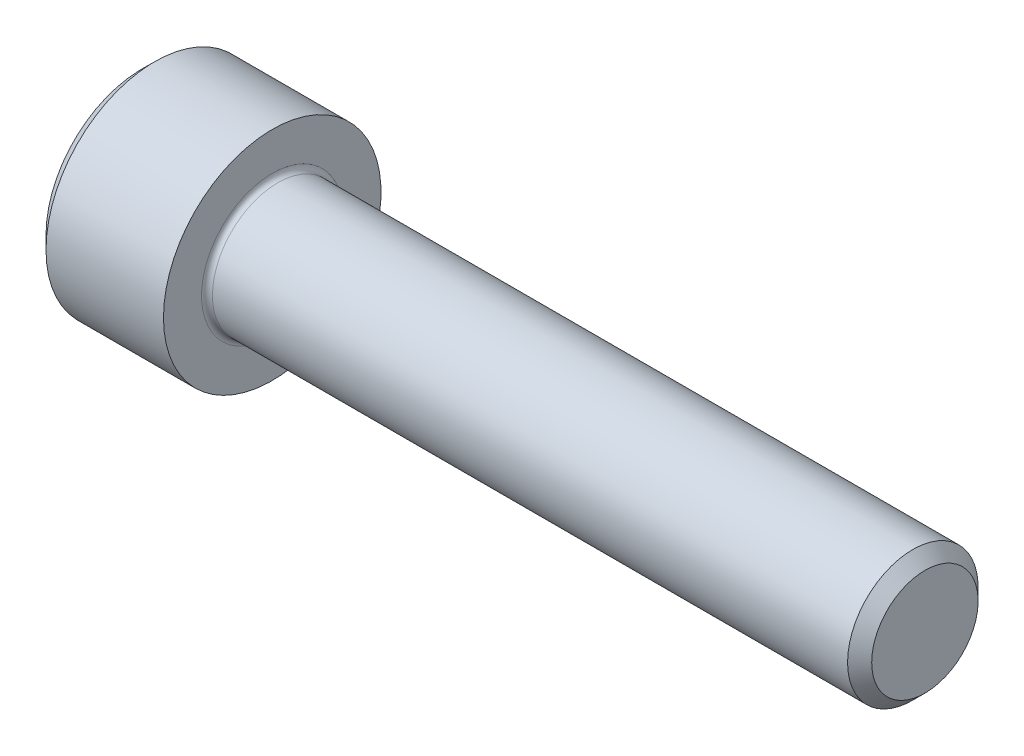
SolidWorks part; units mm, degrees
revolve "Base-Revolve" add sketch "BodySke"
sketch "BodySke" plane through (0, 0, 0) normal (0, 0, 1) x (1, 0, 0)
  line L0 (0, 0) -> (0, 4.4)
  line L1 (0.6, 5) -> (6, 5)
  line L2 (6, 5) -> (6, 3)
  line L3 (6, 3) -> (35.4455, 3)
  line L4 (36, 2.4455) -> (36, 0)
  line L5 (36, 0) -> (0, 0)
  line L6 (-31.75, 0) -> (127, 0) construction
  line L7 (0, 4.4) -> (0.6, 5)
  line L8 (36, 2.4455) -> (35.4455, 3)
  line L9 (0, -4.4) -> (0.6, -5) construction
  line L10 (36, -2.4455) -> (35.4455, -3) construction
  line L11 (7, 1.6185) -> (7, -4.7315) construction
  line L12 (6, 1.6185) -> (6, -4.7315) construction
  line L13 (-14, 1.6185) -> (-14, -4.7315) construction
  dimension "Diameter" = 6
  dimension "Head_ht" = 6
  dimension "Length" = 30
  dimension "Body_ch_ang" = 45
  dimension "Head_dia" = 10
  dimension "Head_ch_ang" = 45
  dimension "Minor_dia" = 4.891
  dimension "Advance" = 1
  dimension "Thread_nom" = 30
  dimension "Thread_length" = 50
  dimension "Head_ch_ht" = 0.6
cosmetic thread "ThreadCosmetic" [suppressed]
fillet "Fillet1" radius 0.25 1 edges at (6, 0, 3)
ref_plane "Plane1" through (0, 0, 0) normal (0, 0, 1) x (1, 0, 0)
ref_plane "Plane2" through (0, 0, 0) normal (0, 1, 0) x (1, 0, 0)
ref_plane "Plane3" through (0, 0, 0) normal (1, 0, 0) x (0, 0, -1)
other "Configuration Table"
sketch "Sketch2" plane through (0, 0, 0) normal (0, 0, 1) x (1, 0, 0)
  line L0 (0, 2.542) -> (3, 2.542)
  line L1 (3, 2.542) -> (4.4676, 0)
  line L2 (-31.75, 0) -> (127, 0) construction
  line L3 (4.4676, 0) -> (0, 0)
  line L4 (0, 0) -> (0, 2.542)
  line L5 (0, 4.4) -> (0, -4.4) construction
  line L6 (0, 0) -> (47.625, 0) construction
  line L7 (6, -5) -> (6, 5) construction
  dimension "D1" = 2.542
  dimension "D2" = 60
revolve "Hex-PreBroach" cut sketch "Sketch2" angle 360 about L6
sketch "Sketch3" plane through (0, 0, 0) normal (-1, 0, 0) x (0, 0.5, 0.866)
  line L0 (1.4676, 2.542) -> (-1.4676, 2.542)
  line L1 (-1.4676, 2.542) -> (-2.9352, 0)
  line L2 (1.4676, 2.542) -> (2.9352, 0)
  line L3 (1.4676, -2.542) -> (2.9352, 0)
  line L4 (1.4676, -2.542) -> (-1.4676, -2.542)
  line L5 (-1.4676, -2.542) -> (-2.9352, 0)
  dimension "D1" = 2.542
  dimension "D2" = 2.542
  dimension "Hex_size" = 5.084
extrude "Hex" cut sketch "Sketch3" against normal blind 3
sketch "Sketch4" plane through (0, 0, 0) normal (-1, 0, 0) x (0, 0, 1)
  line L0 (0, 0) -> (2.8067, 0)
  line L1 (0, 0) -> (6.1484, 3.5498) construction
  line L2 (0, 0) -> (1.4033, 2.4307)
  line L3 (2.3336, 0.614) -> (2.6851, 0.817)
  line L4 (1.6986, 1.7139) -> (2.0501, 1.9169)
  arc A0 (2.3336, 0.614) -> (1.6986, 1.7139) centre (0, 0) ccw
  arc A1 (2.8067, 0) -> (2.6851, 0.817) centre (0, 0) ccw
  arc A2 (1.4033, 2.4307) -> (2.0501, 1.9169) centre (0, 0) cw
  dimension "D2" = 60
  dimension "D1" = 30
  dimension "Spline_p_dim" = 1.27
  dimension "D3" = 0.635
extrude "Spline" [suppressed] cut sketch "Sketch4" against normal blind 3
pattern_circular "CirPattern1" [suppressed] count 6 every 60
sketch "Sketch5" plane through (0, 0, 0) normal (0, 0, 1) x (1, 0, 0)
  line L0 (-31.75, 0) -> (127, 0) construction
  line L2 (0, 4.4) -> (0, -4.4) construction
  circle A0 centre (2.3, 0) radius 0.675
  dimension "Drilled_hole_dia" = 1.35
  dimension "Drilled_hole_loc" = 2.3
extrude "Hole" [suppressed] cut sketch "Sketch5" against normal through all and the other way through all
pattern_circular "Drilled-4" [suppressed] count 2 every 60
pattern_circular "Drilled-6" [suppressed] count 3 every 60
sketch "ThdSchSke" plane through (0, 0, 0) normal (0, 0, 1) x (1, 0, 0)
  line L0 (7, -2.4455) -> (6.6117, -3)
  line L1 (7, -2.4455) -> (7.3883, -3)
  line L2 (7.3883, -3) -> (7.3883, -3.75)
  line L3 (-3.175, 0) -> (5.1513, 0) construction
  line L5 (7.3883, -3.75) -> (6.6117, -3.75)
  line L6 (6.6117, -3.75) -> (6.6117, -3)
  line L7 (0, 4.4) -> (0, -4.4) construction
  dimension "Thread_minor" = 4.891
  dimension "Diameter" = 6
  dimension "Start" = 7
revolve "ThreadSchematic" [suppressed] cut sketch "ThdSchSke" angle 360 about L3
pattern_linear "ThdSchPat" [suppressed]
equation "\"D2@Sketch3\" = \"Hex_size@Sketch3\" / 2"
equation "\"D1@Sketch3\" = \"Hex_size@Sketch3\" / 2"
equation "\"D1@Sketch2\" = \"Hex_size@Sketch3\" / 2"
equation "\"D3@Sketch4\" = \"Spline_p_dim@Sketch4\" / 2"
equation "\"Thread_minor@ThreadCosmetic\"  =  \"Minor_dia@BodySke\""
equation "\"D2@CirPattern1\" = 360 / \"Num_teeth@CirPattern1\""
equation "\"Wall_thickness@Sketch2\" = \"Head_ht@BodySke\" - \"Key_eng@Hex\""
equation "\"Thread_length@ThreadCosmetic\" = ((sgn( (\"Length@BodySke\" - \"Advance@BodySke\" ) - \"Thread_nom@BodySke\" )-1)*( (\"Length@BodySke\" - \"Advance@BodySke\" ) - \"Thread_nom@BodySke\" ))/-2+ \"Thread_nom@BodySke\""
equation "\"Thread_minor@ThdSchSke\" = \"Minor_dia@BodySke\""
equation "\"Diameter@ThdSchSke\" = \"Diameter@BodySke\""
equation "\"Overcut@ThdSchSke\" = \"Diameter@BodySke\" * 1.25"
equation "\"Start@ThdSchSke\" = \"Head_ht@BodySke\" + \"Length@BodySke\" - \"Thread_length@ThreadCosmetic\"  '---Non-countersunk---"
equation "\"Num_threads@ThdSchPat\" = int( \"Thread_length@ThreadCosmetic\" / \"Advance@BodySke\" + 0.999 )  + 1"
equation "\"Advance@ThdSchPat\" = \"Thread_length@ThreadCosmetic\" /  (\"Num_threads@ThdSchPat\" - 1) 'relax it"
equation "\"Num_threads@ThdSchPat\" = \"Num_threads@ThdSchPat\" - sgn( \"Num_threads@ThdSchPat\" - 1) '---chamfered tips only---"
